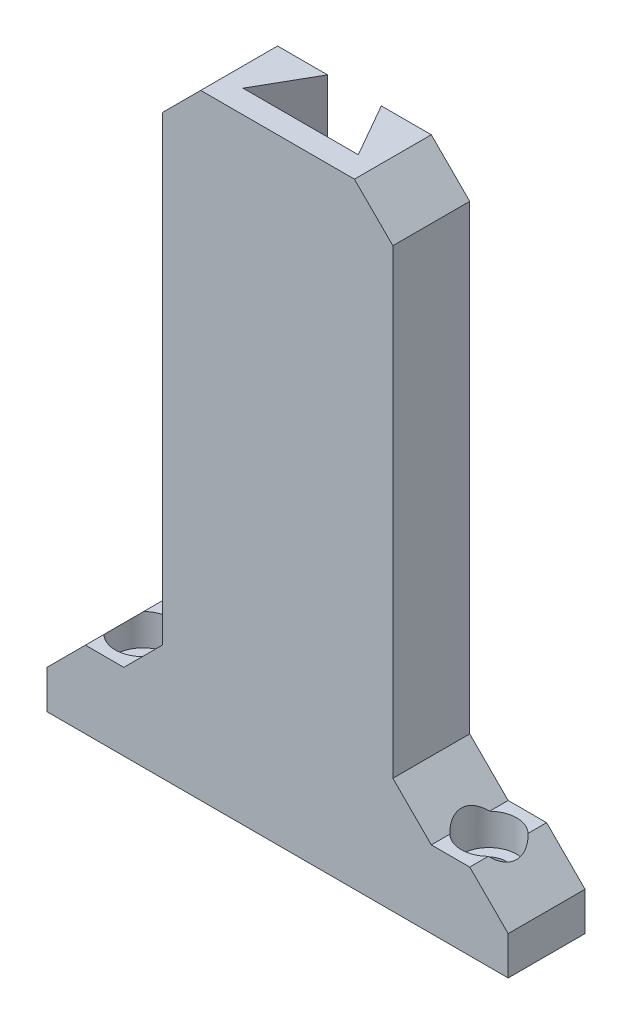
SolidWorks part; units mm, degrees
ref_plane "Front Plane" through (0, 0, 0) normal (0, 0, 1) x (1, 0, 0)
ref_plane "Top Plane" through (0, 0, 0) normal (0, 1, 0) x (1, 0, 0)
ref_plane "Right Plane" through (0, 0, 0) normal (1, 0, 0) x (0, 0, -1)
sketch "Sketch1" plane through (0, 0, 0) normal (0, 0, 1) x (1, 0, 0)
  line L1 (30, 5) -> (-30, 5)
  line L2 (30, 5) -> (30, -5)
  line L3 (30, -5) -> (-30, -5)
  line L4 (-30, 5) -> (-30, -5)
  line L5 (30, 5) -> (-30, -5) construction
  line L6 (30, -5) -> (-30, 5) construction
  line L7 (-15, -5) -> (15, -5)
  line L8 (-15, -5) -> (-15, 75)
  line L9 (-15, 75) -> (15, 75)
  line L10 (15, -5) -> (15, 75)
  point P0 (0, 0)
  point P10 (0, -5)
  point P11 (0, -5)
  dimension "D1" = 10
  dimension "D2" = 60
  dimension "D3" = 30
  dimension "D4" = 80
extrude "Boss-Extrude1" add sketch "Sketch1" along normal blind 10 contours L1 L10 L9 L8 | L10 L3 L2 L1 | L3 L10 L1 L8 | L3 L8 L1 L4
chamfer "Chamfer1" distance 5 angle 45 6 edges at (15, 75, 5) (-15, 75, 5) (-30, 5, 5) (-15, 5, 5) (30, 5, 5) (15, 5, 5)
sketch "Sketch2" plane through (0, 75, 0) normal (0, 1, 0) x (1, 0, 0)
  line L0 (7.5002, -7) -> (-7.5002, -7)
  line L1 (-7.5002, -7) -> (-3.5, 0)
  line L2 (-10, 0) -> (10, 0) construction
  line L3 (-3.5, 0) -> (3.5, 0)
  line L4 (3.5, 0) -> (7.5002, -7)
  line L5 (-15, 0) -> (-10, 0) construction
  point P3 (0, -7)
  point P8 (-15, 0)
  point P11 (0, 0)
  point P12 (2.8315, -5.2156)
  point P13 (0, 0)
  dimension "D1" = 15.0005
  dimension "D2" = 7
  dimension "D3" = 7
extrude "Cut-Extrude1" cut sketch "Sketch2" against normal blind 213
sketch "Sketch3" plane through (0, 5, 0) normal (0, 1, 0) x (1, 0, 0)
  line L0 (20, 0) -> (20, -10) construction
  line L1 (0, -5.5) -> (0, 5.5) construction
  line L2 (25, 0) -> (20, 0) construction
  circle A0 centre (22.5, -5) radius 2.1
  circle A1 centre (-22.5, -5) radius 2.1
  dimension "D2" = 4.2
  dimension "D1" = 2.5
  dimension "D3" = 5
extrude "Cut-Extrude2" cut sketch "Sketch3" against normal blind 213
sketch "Sketch4" plane through (0, 5, 0) normal (0, 1, 0) x (1, 0, 0)
  line L0 (0, -5.5) -> (0, 5.5) construction
  circle A0 centre (22.5, -5) radius 3.6
  circle A1 centre (-22.5, -5) radius 3.6
  dimension "D1" = 7.2
extrude "Cut-Extrude3" cut sketch "Sketch4" against normal blind 4.1 and the other way blind 213
